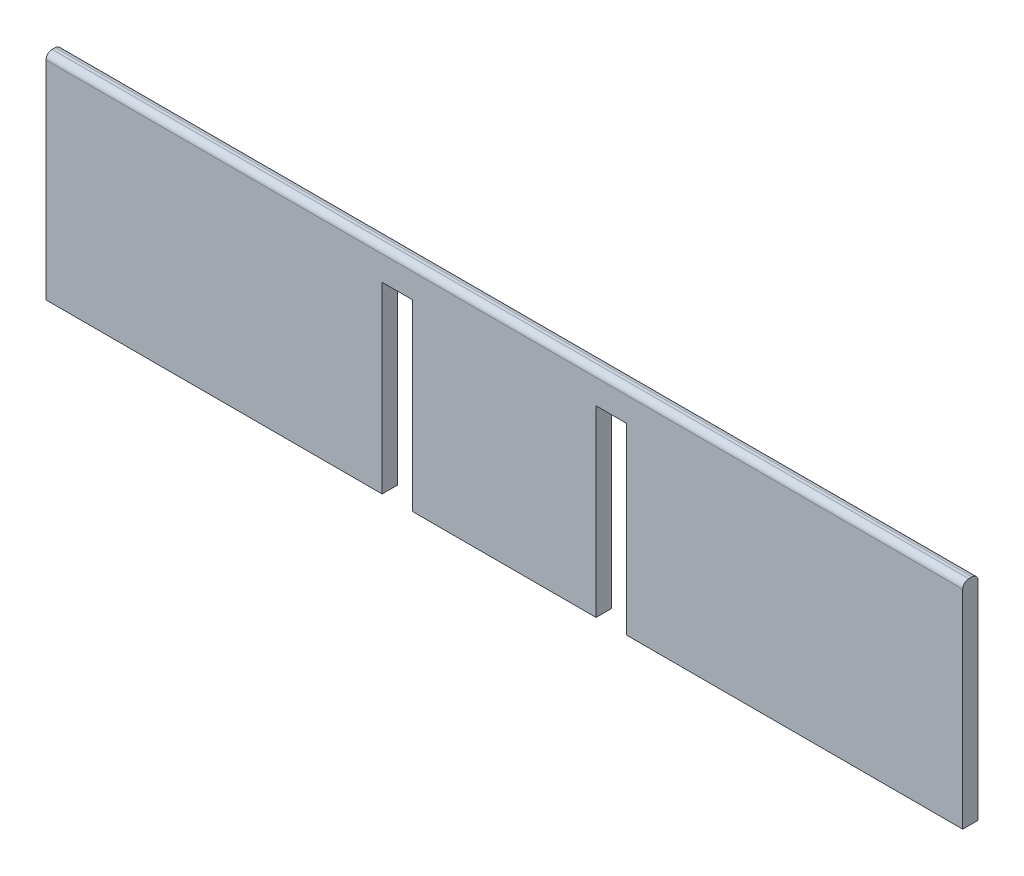
SolidWorks part; units mm, degrees
ref_plane "Plan de face" through (0, 0, 0) normal (0, 0, 1) x (1, 0, 0)
ref_plane "Plan de dessus" through (0, 0, 0) normal (0, 1, 0) x (1, 0, 0)
ref_plane "Plan de droite" through (0, 0, 0) normal (1, 0, 0) x (0, 0, -1)
sketch "Esquisse1" plane through (0, 0, 0) normal (0, 0, 1) x (1, 0, 0)
  line L1 (150, -35) -> (-150, -35)
  line L2 (150, -35) -> (150, 35)
  line L3 (150, 35) -> (-150, 35)
  line L4 (-150, -35) -> (-150, 35)
  line L5 (150, -35) -> (-150, 35) construction
  line L6 (150, 35) -> (-150, -35) construction
  point P0 (0, 0)
  dimension "D1" = 70
  dimension "D2" = 300
extrude "Boss.-Extru.1" add sketch "Esquisse1" along normal blind 5
fillet "Congé2" radius 2 1 edges at (0, 35, 0)
fillet "Congé3" radius 2 1 edges at (0, 35, 5)
sketch "Esquisse2" plane through (0, 0, 0) normal (0, 0, -1) x (-1, 0, 0)
  line L0 (150, -35) -> (-150, -35) construction
  line L5 (-30, -35) -> (-40, -35)
  line L6 (-30, -35) -> (-30, 25)
  line L7 (-30, 25) -> (-40, 25)
  line L8 (-40, -35) -> (-40, 25)
  line L9 (-150, -35) -> (-150, 33) construction
  line L10 (0, 59.7092) -> (0, -56.768) construction
  line L11 (40, -35) -> (40, 25)
  line L12 (30, 25) -> (40, 25)
  line L13 (30, -35) -> (30, 25)
  line L14 (30, -35) -> (40, -35)
  dimension "D1" = 10
  dimension "D2" = 120
  dimension "D3" = 60
extrude "Enlèv. mat.-Extru.1" cut sketch "Esquisse2" against normal through all
